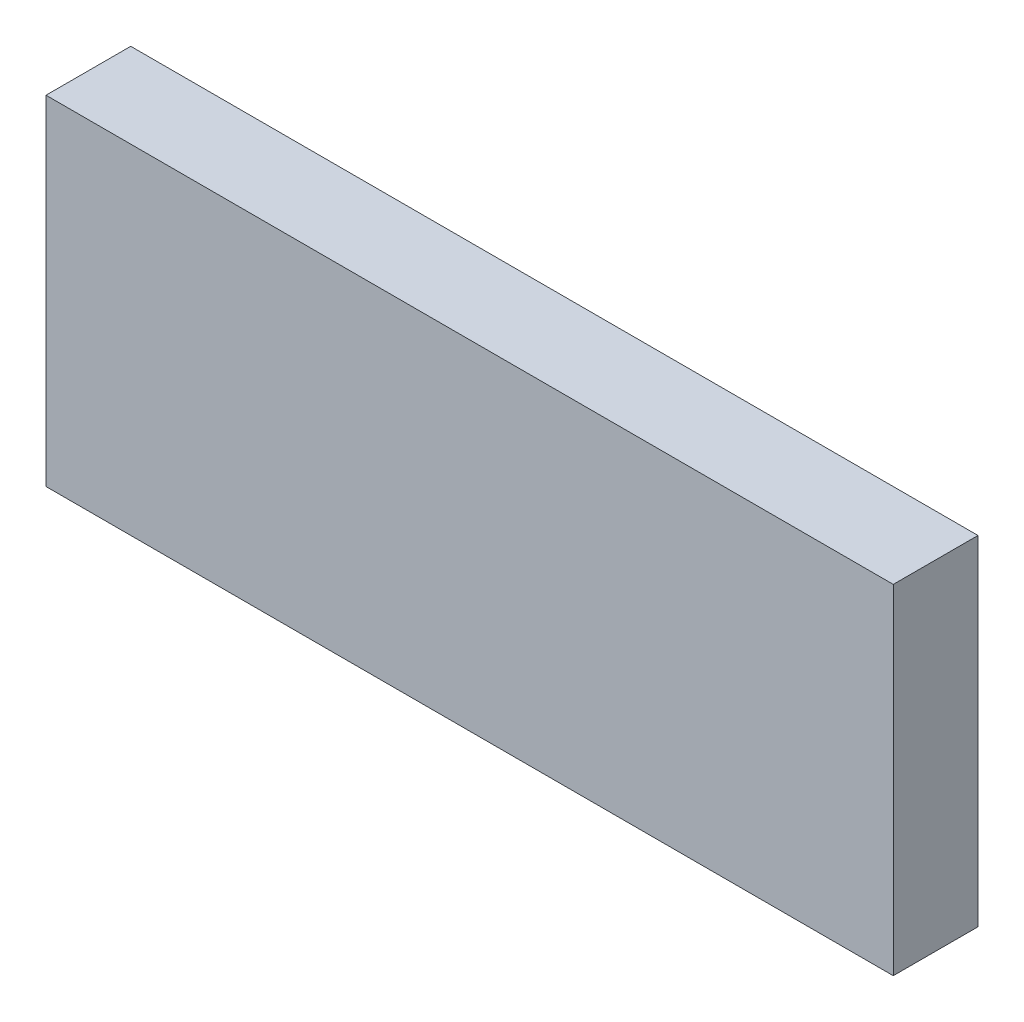
SolidWorks part; units mm, degrees
material "Pino"
ref_plane "Alzado" through (0, 0, 0) normal (0, 0, 1) x (1, 0, 0)
ref_plane "Planta" through (0, 0, 0) normal (0, 1, 0) x (1, 0, 0)
ref_plane "Vista lateral" through (0, 0, 0) normal (1, 0, 0) x (0, 0, -1)
sketch "Croquis2" plane through (0, 0, 0) normal (0, 0, 1) x (1, 0, 0)
  line L1 (0, 0) -> (500, 0)
  line L2 (0, 0) -> (0, 200)
  line L3 (0, 200) -> (500, 200)
  line L4 (500, 0) -> (500, 200)
  dimension "D1" = 200
  dimension "D2" = 500
extrude "Saliente-Extruir1" add sketch "Croquis2" along normal blind 50
